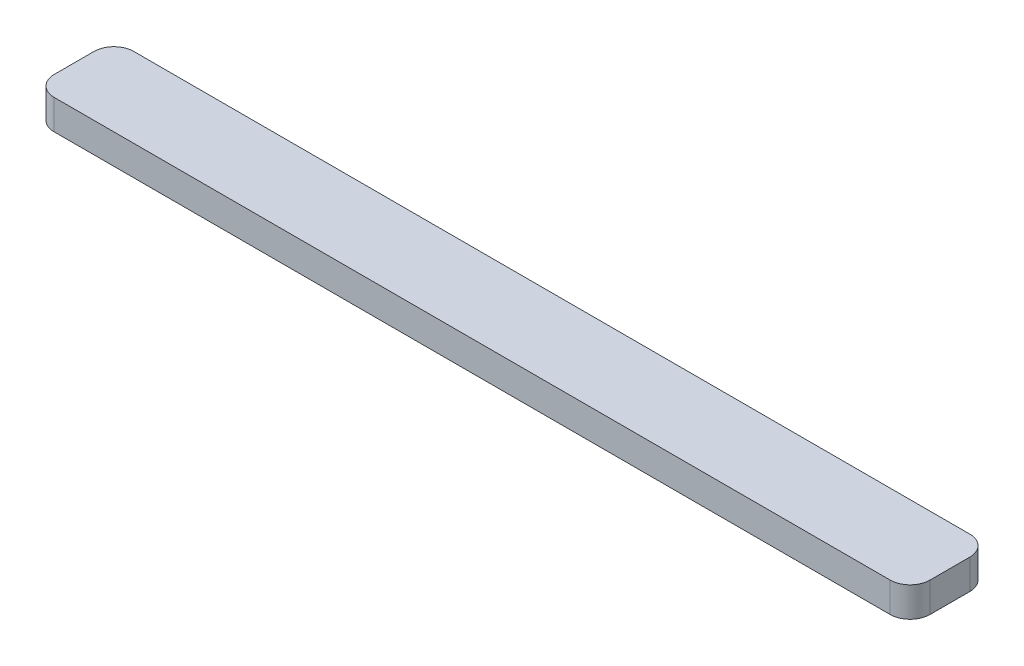
SolidWorks part; units mm, degrees
ref_plane "前视基准面" through (0, 0, 0) normal (0, 0, 1) x (1, 0, 0)
ref_plane "上视基准面" through (0, 0, 0) normal (0, 1, 0) x (1, 0, 0)
ref_plane "右视基准面" through (0, 0, 0) normal (1, 0, 0) x (0, 0, -1)
other "Configuration Table"
sketch "草图1" plane through (0, 0, 0) normal (0, 1, 0) x (1, 0, 0)
  line L1 (42, -4) -> (-42, -4)
  line L2 (44, -2) -> (44, 2)
  line L3 (42, 4) -> (-42, 4)
  line L4 (-44, -2) -> (-44, 2)
  line L5 (44, -4) -> (-44, 4) construction
  line L6 (44, 4) -> (-44, -4) construction
  arc A0 (-44, -2) -> (-42, -4) centre (-42, -2) ccw
  arc A1 (44, -2) -> (42, -4) centre (42, -2) cw
  arc A2 (44, 2) -> (42, 4) centre (42, 2) ccw
  arc A3 (-42, 4) -> (-44, 2) centre (-42, 2) ccw
  point P0 (0, 0)
  dimension "D3" = 2
  dimension "D1" = 8
  dimension "D2" = 88
extrude "凸台-拉伸1" add sketch "草图1" along normal blind 3
